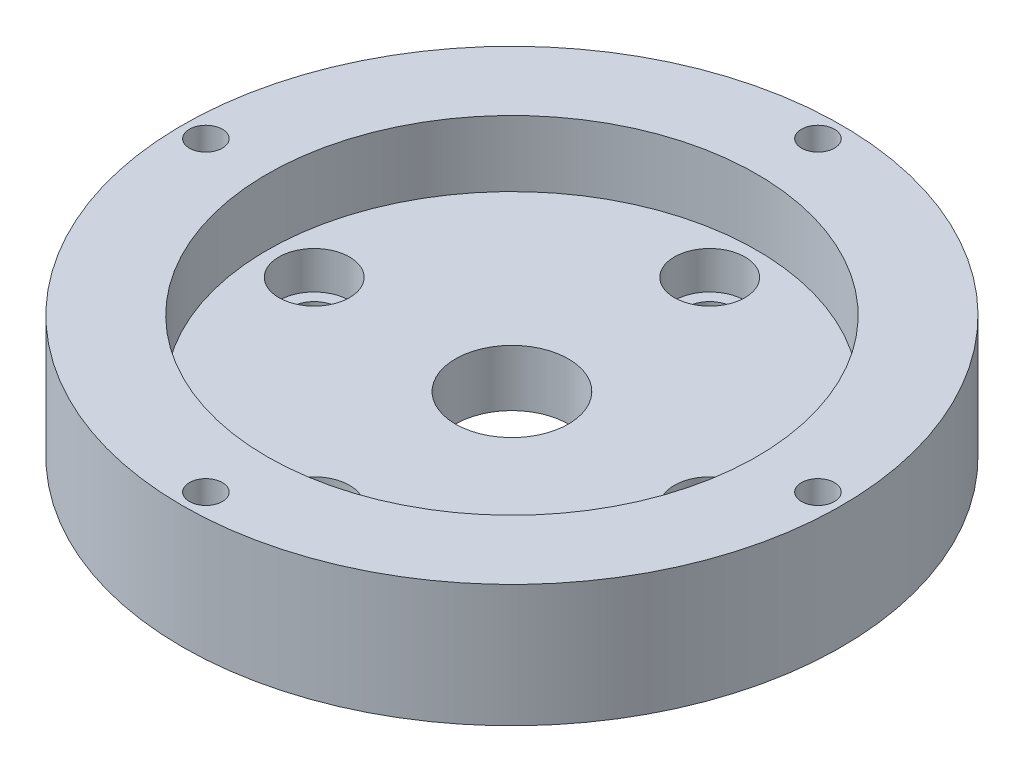
SolidWorks part; units mm, degrees
ref_plane "Front Plane" through (0, 0, 0) normal (0, 0, 1) x (1, 0, 0)
ref_plane "Top Plane" through (0, 0, 0) normal (0, 1, 0) x (1, 0, 0)
ref_plane "Right Plane" through (0, 0, 0) normal (1, 0, 0) x (0, 0, -1)
sketch "Sketch1" plane through (0, 0, 0) normal (0, 1, 0) x (1, 0, 0)
  line L0 (0, 0) -> (-46886.1363, 0) construction
  line L1 (0, 0) -> (0, -46886.1363) construction
  circle A0 centre (0, 0) radius 35
  dimension "D1" = 70
extrude "Boss-Extrude1" add sketch "Sketch1" along normal blind 6
sketch "Sketch2" plane through (0, 6, 0) normal (0, 1, 0) x (1, 0, 0)
  line L0 (0, 0) -> (-50000, 0) construction
  line L1 (0, 0) -> (0, -50000) construction
  circle A0 centre (0, 0) radius 21 construction
  circle A1 centre (0, 21) radius 3.75
  circle A2 centre (21, 0) radius 3.75
  circle A3 centre (0, -21) radius 3.75
  circle A4 centre (-21, 0) radius 3.75
  point P18 (0, 0)
  dimension "D1" = 42
  dimension "D2" = 7.5
  dimension "D3" = 4
extrude "Cut-Extrude1" cut sketch "Sketch2" against normal blind 4
sketch "Sketch3" plane through (0, 6, 0) normal (0, 1, 0) x (1, 0, 0)
  line L0 (0, 0) -> (-50000, 0) construction
  line L1 (0, 0) -> (0, -50000) construction
  circle A0 centre (0, 0) radius 6
  circle A1 centre (0, 21) radius 2.5
  circle A2 centre (21, 0) radius 2.5
  circle A3 centre (0, -21) radius 2.5
  circle A4 centre (-21, 0) radius 2.5
  point P19 (0, 0)
  dimension "D1" = 12
  dimension "D2" = 5
  dimension "D3" = 4
extrude "Cut-Extrude2" cut sketch "Sketch3" against normal through all
sketch "Sketch4" plane through (0, 6, 0) normal (0, 1, 0) x (1, 0, 0)
  line L0 (0, 0) -> (-50000, 0) construction
  line L1 (0, 0) -> (0, -50000) construction
  circle A0 centre (0, 0) radius 35
  circle A1 centre (0, 0) radius 30
  dimension "D1" = 70
  dimension "D2" = 60
extrude "Boss-Extrude2" add sketch "Sketch4" along normal blind 7
sketch "Sketch5" plane through (0, 6, 0) normal (0, 1, 0) x (1, 0, 0)
  line L0 (0, 0) -> (-50000, 0) construction
  line L1 (0, 0) -> (0, -50000) construction
  circle A0 centre (0, 0) radius 30
  circle A1 centre (0, 0) radius 26
  dimension "D1" = 52
  dimension "D2" = 60
extrude "Boss-Extrude3" add sketch "Sketch5" along normal up to surface (7 mm away) up to face at (0, 13, 35)
sketch "Sketch6" plane through (0, 13, 0) normal (0, 1, 0) x (1, 0, 0)
  line L0 (0, 0) -> (-50000, 0) construction
  line L1 (0, 0) -> (0, -50000) construction
  circle A0 centre (0, 0) radius 32.5 construction
  circle A1 centre (0, 32.5) radius 1.75
  circle A2 centre (32.5, 0) radius 1.75
  circle A3 centre (0, -32.5) radius 1.75
  circle A4 centre (-32.5, 0) radius 1.75
  point P18 (0, 0)
  dimension "D1" = 65
  dimension "D2" = 3.5
extrude "Cut-Extrude3" cut sketch "Sketch6" against normal through all
sketch "Sketch7" plane through (0, 0, 0) normal (0, -1, 0) x (1, 0, 0)
  line L0 (0, 0) -> (-50000, 0) construction
  line L1 (0, 0) -> (0, -50000) construction
  circle A0 centre (0, 32.5) radius 2
  circle A1 centre (32.5, 0) radius 2
  circle A2 centre (0, -32.5) radius 2
  circle A3 centre (-32.5, 0) radius 2
  point P17 (0, 0)
  dimension "D1" = 4
extrude "Cut-Extrude4" cut sketch "Sketch7" against normal blind 3
